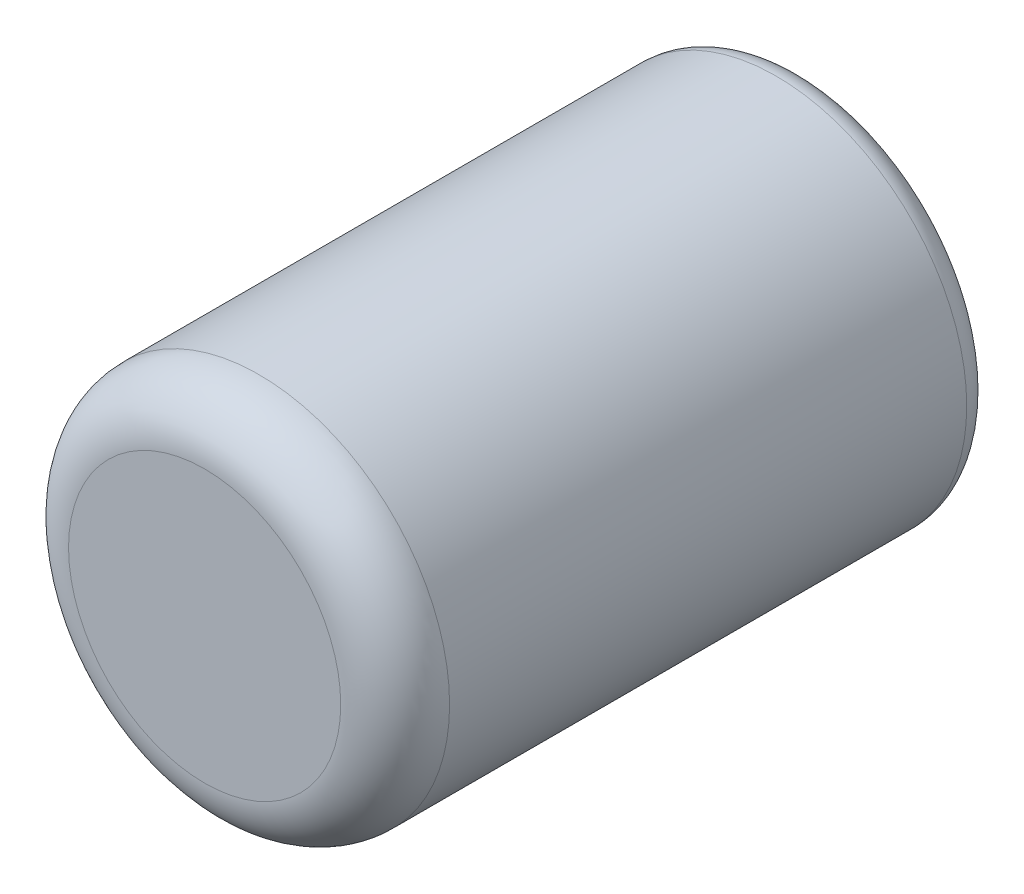
SolidWorks part; units mm, degrees
material "ABS"
ref_plane "Front Plane" through (0, 0, 0) normal (0, 0, 1) x (1, 0, 0)
ref_plane "Top Plane" through (0, 0, 0) normal (0, 1, 0) x (1, 0, 0)
ref_plane "Right Plane" through (0, 0, 0) normal (1, 0, 0) x (0, 0, -1)
sketch "Sketch1" plane through (0, 0, 0) normal (0, 0, 1) x (1, 0, 0)
  circle A0 centre (0, 0) radius 4
  circle A1 centre (0, 0) radius 7
  dimension "D1" = 8
  dimension "D2" = 14
extrude "Boss-Extrude1" add sketch "Sketch1" along normal blind 20
sketch "Sketch2" plane through (0, 0, 20) normal (0, 0, 1) x (1, 0, 0)
  circle A1 centre (0, 0) radius 7
  circle A2 centre (0, 0) radius 7
  dimension "D1" = 0
extrude "Boss-Extrude2" add sketch "Sketch2" along normal blind 2
fillet "Fillet1" radius 2 1 edges at (7, 0, 22)
fillet "Fillet2" radius 1 1 edges at (7, 0, 0)
